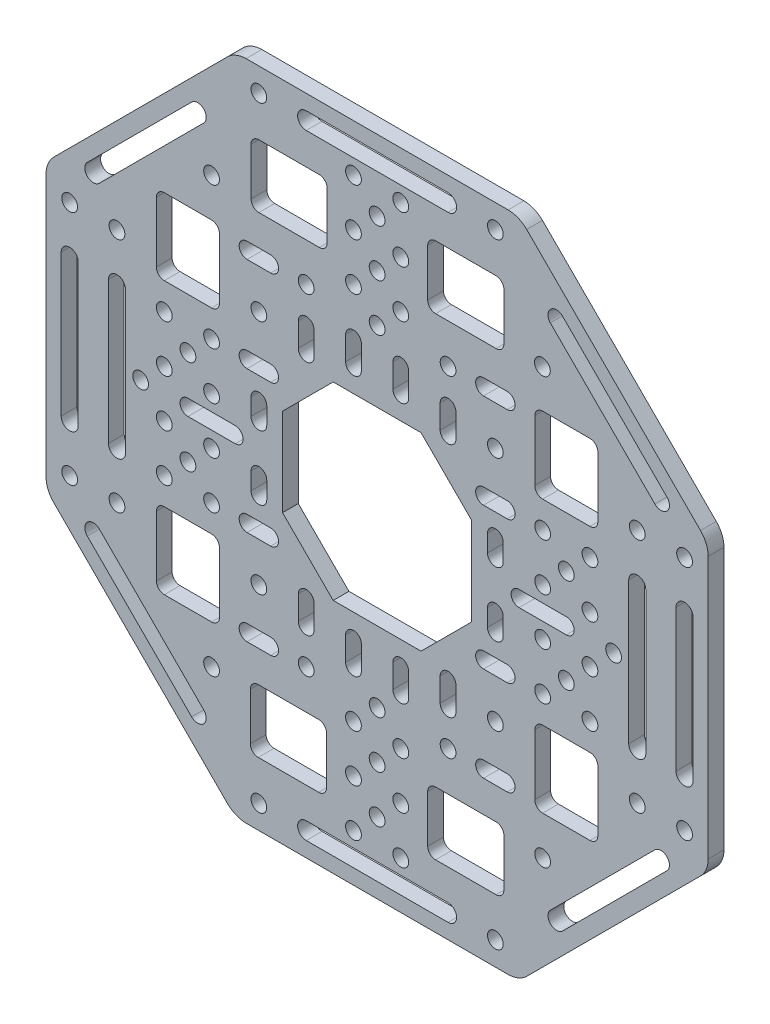
SolidWorks part; units mm, degrees
ref_plane "Alzado" through (0, 0, 0) normal (0, 0, 1) x (1, 0, 0)
ref_plane "Planta" through (0, 0, 0) normal (0, 1, 0) x (1, 0, 0)
ref_plane "Vista lateral" through (0, 0, 0) normal (1, 0, 0) x (0, 0, -1)
sketch "Model" plane through (0, 0, 0) normal (0, 0, 1) x (1, 0, 0)
  line L0 (181.0281, 257.4957) -> (131.1702, 257.4957)
  line L1 (217.6323, 222.9625) -> (184.5636, 256.0312)
  line L2 (219.0991, 169.5667) -> (219.0991, 219.4246)
  line L3 (184.5636, 132.9601) -> (217.6323, 166.0288)
  line L4 (131.1702, 131.4957) -> (181.0281, 131.4957)
  line L5 (94.566, 166.0288) -> (127.6347, 132.9601)
  line L6 (127.6347, 256.0312) -> (94.566, 222.9625)
  line L7 (174.0991, 202.8561) -> (164.4595, 212.4957)
  line L8 (174.0991, 186.1353) -> (174.0991, 202.8561)
  line L9 (164.4595, 176.4957) -> (174.0991, 186.1353)
  line L10 (147.7387, 176.4957) -> (164.4595, 176.4957)
  line L11 (138.0991, 186.1353) -> (147.7387, 176.4957)
  line L12 (138.0991, 202.8561) -> (138.0991, 186.1353)
  line L13 (147.7387, 212.4957) -> (138.0991, 202.8561)
  line L14 (164.4595, 212.4957) -> (147.7387, 212.4957)
  line L15 (93.0991, 219.4246) -> (93.0991, 169.5667)
  line L19 (142.5991, 254.6207) -> (169.5991, 254.6207)
  line L20 (169.5991, 251.3707) -> (142.5991, 251.3707)
  line L21 (123.1463, 242.8905) -> (103.2482, 222.9897)
  line L22 (100.9501, 225.2878) -> (120.7725, 245.1102)
  line L23 (95.9741, 207.9957) -> (95.9741, 180.9957)
  line L24 (99.2241, 180.9957) -> (99.2241, 207.9957)
  line L25 (104.9741, 207.9957) -> (104.9741, 180.9957)
  line L26 (108.2241, 180.9957) -> (108.2241, 207.9957)
  line L27 (203.9741, 207.9957) -> (203.9741, 180.9957)
  line L28 (207.2241, 180.9957) -> (207.2241, 207.9957)
  line L29 (212.9741, 207.9957) -> (212.9741, 180.9957)
  line L30 (216.2241, 180.9957) -> (216.2241, 207.9957)
  line L31 (208.9501, 222.9897) -> (189.052, 242.8905)
  line L32 (191.4258, 245.1102) -> (211.2482, 225.2878)
  line L33 (103.2139, 166.0348) -> (123.1041, 146.1447)
  line L34 (120.806, 143.8466) -> (100.9501, 163.7035)
  line L35 (142.5991, 137.6207) -> (169.5991, 137.6207)
  line L36 (142.5991, 134.3707) -> (169.5991, 134.3707)
  line L37 (189.0942, 146.1447) -> (208.9501, 166.0016)
  line L38 (211.2461, 163.7014) -> (191.3923, 143.8466)
  line L39 (131.3491, 227.4957) -> (135.8491, 227.4957)
  line L40 (135.8491, 224.4957) -> (131.3491, 224.4957)
  line L41 (141.0991, 219.2457) -> (141.0991, 214.7457)
  line L42 (144.0991, 214.7457) -> (144.0991, 219.2457)
  line L43 (150.0991, 221.4957) -> (150.0991, 216.9957)
  line L44 (153.0991, 216.9957) -> (153.0991, 221.4957)
  line L45 (159.0991, 221.4957) -> (159.0991, 216.9957)
  line L46 (162.0991, 216.9957) -> (162.0991, 221.4957)
  line L47 (168.0991, 219.2457) -> (168.0991, 214.7457)
  line L48 (171.0991, 214.7457) -> (171.0991, 219.2457)
  line L49 (176.3491, 224.4957) -> (180.8491, 224.4957)
  line L50 (176.3491, 227.4957) -> (180.8491, 227.4957)
  line L51 (176.3491, 209.4957) -> (180.8491, 209.4957)
  line L52 (180.8491, 206.4957) -> (176.3491, 206.4957)
  line L53 (177.0991, 202.2457) -> (177.0991, 198.9957)
  line L54 (180.0991, 198.9957) -> (180.0991, 202.2457)
  line L55 (183.0991, 195.9957) -> (192.0991, 195.9957)
  line L56 (192.0991, 192.9957) -> (183.0991, 192.9957)
  line L57 (180.0991, 189.9957) -> (180.0991, 186.7457)
  line L58 (177.0991, 186.7457) -> (177.0991, 189.9957)
  line L59 (176.3491, 182.4957) -> (180.8491, 182.4957)
  line L60 (180.8491, 179.4957) -> (176.3491, 179.4957)
  line L61 (171.0991, 174.2457) -> (171.0991, 169.7457)
  line L62 (168.0991, 169.7457) -> (168.0991, 174.2457)
  line L63 (162.0991, 171.9957) -> (162.0991, 167.4957)
  line L64 (159.0991, 167.4957) -> (159.0991, 171.9957)
  line L65 (153.0991, 171.9957) -> (153.0991, 167.4957)
  line L66 (150.0991, 167.4957) -> (150.0991, 171.9957)
  line L67 (144.0991, 174.2457) -> (144.0991, 169.7457)
  line L68 (141.0991, 169.7457) -> (141.0991, 174.2457)
  line L69 (131.3491, 164.4957) -> (135.8491, 164.4957)
  line L70 (135.8491, 161.4957) -> (131.3491, 161.4957)
  line L71 (131.3491, 179.4957) -> (135.8491, 179.4957)
  line L72 (135.8491, 182.4957) -> (131.3491, 182.4957)
  line L73 (132.0991, 186.7457) -> (132.0991, 189.9957)
  line L74 (135.0991, 189.9957) -> (135.0991, 186.7457)
  line L75 (129.0991, 192.9957) -> (120.0991, 192.9957)
  line L76 (120.0991, 195.9957) -> (129.0991, 195.9957)
  line L77 (132.0991, 202.2457) -> (132.0991, 198.9957)
  line L78 (135.0991, 198.9957) -> (135.0991, 202.2457)
  line L79 (135.8491, 206.4957) -> (131.3491, 206.4957)
  line L80 (131.3491, 209.4957) -> (135.8491, 209.4957)
  line L81 (132.1048, 243.8415) -> (132.1048, 234.8415)
  line L82 (133.6048, 233.3415) -> (145.1048, 233.3415)
  line L83 (146.6048, 234.8415) -> (146.6048, 243.8415)
  line L84 (145.1048, 245.3415) -> (133.6048, 245.3415)
  line L85 (131.9741, 153.9957) -> (131.9741, 144.9957)
  line L86 (133.4741, 143.4957) -> (144.9741, 143.4957)
  line L87 (146.4741, 144.9957) -> (146.4741, 153.9957)
  line L88 (144.9741, 155.4957) -> (133.4741, 155.4957)
  line L89 (165.7241, 153.9957) -> (165.7241, 144.9957)
  line L90 (167.2241, 143.4957) -> (178.7241, 143.4957)
  line L91 (180.2241, 144.9957) -> (180.2241, 153.9957)
  line L92 (178.7241, 155.4957) -> (167.2241, 155.4957)
  line L93 (165.7241, 243.9957) -> (165.7241, 234.9957)
  line L94 (167.2241, 233.4957) -> (178.7241, 233.4957)
  line L95 (180.2241, 234.9957) -> (180.2241, 243.9957)
  line L96 (178.7241, 245.4957) -> (167.2241, 245.4957)
  line L97 (115.5991, 213.1207) -> (124.5991, 213.1207)
  line L98 (126.0991, 214.6207) -> (126.0991, 226.1207)
  line L99 (124.5991, 227.6207) -> (115.5991, 227.6207)
  line L100 (114.0991, 226.1207) -> (114.0991, 214.6207)
  line L101 (115.5991, 161.3707) -> (124.5991, 161.3707)
  line L102 (126.0991, 162.8707) -> (126.0991, 174.3707)
  line L103 (124.5991, 175.8707) -> (115.5991, 175.8707)
  line L104 (114.0991, 174.3707) -> (114.0991, 162.8707)
  line L105 (187.5991, 213.1207) -> (196.5991, 213.1207)
  line L106 (198.0991, 214.6207) -> (198.0991, 226.1207)
  line L107 (196.5991, 227.6207) -> (187.5991, 227.6207)
  line L108 (186.0991, 226.1207) -> (186.0991, 214.6207)
  line L109 (187.5991, 161.3707) -> (196.5991, 161.3707)
  line L110 (198.0991, 162.8707) -> (198.0991, 174.3707)
  line L111 (196.5991, 175.8707) -> (187.5991, 175.8707)
  line L112 (186.0991, 174.3707) -> (186.0991, 162.8707)
  line L113 (176.3491, 164.4957) -> (180.8491, 164.4957)
  line L114 (176.3491, 161.4957) -> (180.8491, 161.4957)
  arc A0 (131.1702, 257.4957) -> (127.6347, 256.0312) centre (131.2301, 252.3511) ccw
  arc A1 (184.5636, 256.0312) -> (181.0281, 257.4957) centre (180.9681, 252.3511) ccw
  arc A2 (219.0991, 219.4246) -> (217.6323, 222.9625) centre (214.0991, 219.4246) ccw
  arc A3 (217.6323, 166.0288) -> (219.0991, 169.5667) centre (214.0991, 169.5667) ccw
  arc A4 (181.0281, 131.4957) -> (184.5636, 132.9601) centre (180.9682, 136.6403) ccw
  arc A5 (127.6347, 132.9601) -> (131.1702, 131.4957) centre (131.2301, 136.6403) ccw
  arc A6 (93.0991, 169.5667) -> (94.566, 166.0288) centre (98.0991, 169.5667) ccw
  arc A7 (94.566, 222.9625) -> (93.0991, 219.4246) centre (98.0991, 219.4246) ccw
  arc A8 (95.9741, 180.9957) -> (99.2241, 180.9957) centre (97.5991, 180.9957) ccw
  arc A9 (99.2241, 207.9957) -> (95.9741, 207.9957) centre (97.5991, 207.9957) ccw
  arc A10 (192.0991, 192.9957) -> (192.0991, 195.9957) centre (192.0991, 194.4957) ccw
  arc A11 (183.0991, 195.9957) -> (183.0991, 192.9957) centre (183.0991, 194.4957) ccw
  arc A12 (177.0991, 198.9957) -> (180.0991, 198.9957) centre (178.5991, 198.9957) ccw
  arc A13 (180.0991, 202.2457) -> (177.0991, 202.2457) centre (178.5991, 202.2457) ccw
  arc A14 (177.0991, 186.7457) -> (180.0991, 186.7457) centre (178.5991, 186.7457) ccw
  arc A15 (180.0991, 189.9957) -> (177.0991, 189.9957) centre (178.5991, 189.9957) ccw
  circle A16 centre (120.0991, 185.4957) radius 1.5
  circle A17 centre (120.0991, 203.4957) radius 1.5
  circle A18 centre (192.0991, 203.4957) radius 1.5
  circle A19 centre (192.0991, 185.4957) radius 1.5
  arc A20 (132.0991, 198.9957) -> (135.0991, 198.9957) centre (133.5991, 198.9957) ccw
  arc A21 (135.0991, 202.2457) -> (132.0991, 202.2457) centre (133.5991, 202.2457) ccw
  arc A22 (132.0991, 186.7457) -> (135.0991, 186.7457) centre (133.5991, 186.7457) ccw
  arc A23 (135.0991, 189.9957) -> (132.0991, 189.9957) centre (133.5991, 189.9957) ccw
  circle A24 centre (187.5991, 189.9957) radius 1.5
  circle A25 centre (187.5991, 198.9957) radius 1.5
  circle A26 centre (124.5991, 189.9957) radius 1.5
  circle A27 centre (124.5991, 198.9957) radius 1.5
  circle A28 centre (187.5991, 153.9957) radius 1.5
  circle A29 centre (160.5991, 149.4957) radius 1.5
  circle A30 centre (151.5991, 149.4957) radius 1.5
  circle A31 centre (156.0991, 153.9957) radius 1.5
  circle A32 centre (156.0991, 144.9957) radius 1.5
  circle A33 centre (124.5991, 153.9957) radius 1.5
  circle A34 centre (187.5991, 180.9957) radius 1.5
  circle A35 centre (196.5991, 180.9957) radius 1.5
  circle A36 centre (205.5991, 171.9957) radius 1.5
  circle A37 centre (196.5991, 198.9957) radius 1.5
  circle A38 centre (201.0991, 194.4957) radius 1.5
  circle A39 centre (196.5991, 189.9957) radius 1.5
  circle A40 centre (187.5991, 207.9957) radius 1.5
  circle A41 centre (196.5991, 207.9957) radius 1.5
  circle A42 centre (205.5991, 216.9957) radius 1.5
  circle A43 centre (187.552, 234.9195) radius 1.5
  circle A44 centre (169.5991, 162.9957) radius 1.5
  circle A45 centre (178.5991, 171.9957) radius 1.5
  circle A46 centre (133.5991, 171.9957) radius 1.5
  circle A47 centre (142.5991, 162.9957) radius 1.5
  circle A48 centre (156.0991, 162.9957) radius 1.5
  circle A49 centre (160.5991, 230.4957) radius 1.5
  circle A50 centre (178.5991, 216.9957) radius 1.5
  circle A51 centre (169.5991, 225.9957) radius 1.5
  circle A52 centre (160.5991, 239.4957) radius 1.5
  circle A53 centre (133.5991, 216.9957) radius 1.5
  circle A54 centre (142.5991, 225.9957) radius 1.5
  circle A55 centre (151.5991, 230.4957) radius 1.5
  circle A56 centre (151.5991, 239.4957) radius 1.5
  circle A57 centre (156.0991, 243.9957) radius 1.5
  circle A58 centre (156.0991, 225.9957) radius 1.5
  circle A59 centre (156.0991, 234.9957) radius 1.5
  circle A60 centre (106.5991, 171.9957) radius 1.5
  circle A61 centre (115.5991, 180.9957) radius 1.5
  circle A62 centre (124.5991, 180.9957) radius 1.5
  circle A63 centre (115.5991, 198.9957) radius 1.5
  circle A64 centre (115.5991, 189.9957) radius 1.5
  circle A65 centre (111.0991, 194.4957) radius 1.5
  circle A66 centre (106.5991, 216.9957) radius 1.5
  circle A67 centre (124.5991, 234.9957) radius 1.5
  circle A68 centre (115.5991, 207.9957) radius 1.5
  circle A69 centre (124.5991, 207.9957) radius 1.5
  circle A70 centre (151.5991, 158.4957) radius 1.5
  circle A71 centre (160.5991, 158.4957) radius 1.5
  arc A72 (144.0991, 219.2457) -> (141.0991, 219.2457) centre (142.5991, 219.2457) ccw
  arc A73 (141.0991, 214.7457) -> (144.0991, 214.7457) centre (142.5991, 214.7457) ccw
  arc A74 (135.8491, 161.4957) -> (135.8491, 164.4957) centre (135.8491, 162.9957) ccw
  arc A75 (131.3491, 164.4957) -> (131.3491, 161.4957) centre (131.3491, 162.9957) ccw
  arc A76 (216.2241, 207.9957) -> (212.9741, 207.9957) centre (214.5991, 207.9957) ccw
  arc A77 (212.9741, 180.9957) -> (216.2241, 180.9957) centre (214.5991, 180.9957) ccw
  arc A78 (207.2241, 207.9957) -> (203.9741, 207.9957) centre (205.5991, 207.9957) ccw
  arc A79 (203.9741, 180.9957) -> (207.2241, 180.9957) centre (205.5991, 180.9957) ccw
  arc A80 (142.5991, 137.6207) -> (142.5991, 134.3707) centre (142.5991, 135.9957) ccw
  arc A81 (169.5991, 134.3707) -> (169.5991, 137.6207) centre (169.5991, 135.9957) ccw
  arc A82 (176.3491, 227.4957) -> (176.3491, 224.4957) centre (176.3491, 225.9957) ccw
  arc A83 (180.8491, 224.4957) -> (180.8491, 227.4957) centre (180.8491, 225.9957) ccw
  arc A84 (176.3491, 209.4957) -> (176.3491, 206.4957) centre (176.3491, 207.9957) ccw
  arc A85 (180.8491, 206.4957) -> (180.8491, 209.4957) centre (180.8491, 207.9957) ccw
  arc A86 (176.3491, 182.4957) -> (176.3491, 179.4957) centre (176.3491, 180.9957) ccw
  arc A87 (180.8491, 179.4957) -> (180.8491, 182.4957) centre (180.8491, 180.9957) ccw
  arc A88 (176.3491, 164.4957) -> (176.3491, 161.4957) centre (176.3491, 162.9957) ccw
  arc A89 (180.8491, 161.4957) -> (180.8491, 164.4957) centre (180.8491, 162.9957) ccw
  arc A90 (168.0991, 169.7457) -> (171.0991, 169.7457) centre (169.5991, 169.7457) ccw
  arc A91 (171.0991, 174.2457) -> (168.0991, 174.2457) centre (169.5991, 174.2457) ccw
  arc A92 (171.0991, 219.2457) -> (168.0991, 219.2457) centre (169.5991, 219.2457) ccw
  arc A93 (168.0991, 214.7457) -> (171.0991, 214.7457) centre (169.5991, 214.7457) ccw
  arc A94 (142.5991, 254.6207) -> (142.5991, 251.3707) centre (142.5991, 252.9957) ccw
  arc A95 (169.5991, 251.3707) -> (169.5991, 254.6207) centre (169.5991, 252.9957) ccw
  arc A96 (159.0991, 167.4957) -> (162.0991, 167.4957) centre (160.5991, 167.4957) ccw
  arc A97 (162.0991, 171.9957) -> (159.0991, 171.9957) centre (160.5991, 171.9957) ccw
  arc A98 (162.0991, 221.4957) -> (159.0991, 221.4957) centre (160.5991, 221.4957) ccw
  arc A99 (159.0991, 216.9957) -> (162.0991, 216.9957) centre (160.5991, 216.9957) ccw
  arc A100 (153.0991, 221.4957) -> (150.0991, 221.4957) centre (151.5991, 221.4957) ccw
  arc A101 (150.0991, 216.9957) -> (153.0991, 216.9957) centre (151.5991, 216.9957) ccw
  arc A102 (150.0991, 167.4957) -> (153.0991, 167.4957) centre (151.5991, 167.4957) ccw
  arc A103 (153.0991, 171.9957) -> (150.0991, 171.9957) centre (151.5991, 171.9957) ccw
  arc A104 (141.0991, 169.7457) -> (144.0991, 169.7457) centre (142.5991, 169.7457) ccw
  arc A105 (144.0991, 174.2457) -> (141.0991, 174.2457) centre (142.5991, 174.2457) ccw
  arc A106 (135.8491, 224.4957) -> (135.8491, 227.4957) centre (135.8491, 225.9957) ccw
  arc A107 (131.3491, 227.4957) -> (131.3491, 224.4957) centre (131.3491, 225.9957) ccw
  arc A108 (135.8491, 206.4957) -> (135.8491, 209.4957) centre (135.8491, 207.9957) ccw
  arc A109 (131.3491, 209.4957) -> (131.3491, 206.4957) centre (131.3491, 207.9957) ccw
  arc A110 (135.8491, 179.4957) -> (135.8491, 182.4957) centre (135.8491, 180.9957) ccw
  arc A111 (131.3491, 182.4957) -> (131.3491, 179.4957) centre (131.3491, 180.9957) ccw
  arc A112 (129.0991, 192.9957) -> (129.0991, 195.9957) centre (129.0991, 194.4957) ccw
  arc A113 (120.0991, 195.9957) -> (120.0991, 192.9957) centre (120.0991, 194.4957) ccw
  arc A114 (108.2241, 207.9957) -> (104.9741, 207.9957) centre (106.5991, 207.9957) ccw
  arc A115 (104.9741, 180.9957) -> (108.2241, 180.9957) centre (106.5991, 180.9957) ccw
  circle A116 centre (160.5991, 248.4957) radius 1.5
  circle A117 centre (151.5991, 248.4957) radius 1.5
  circle A118 centre (160.5991, 140.4957) radius 1.5
  circle A119 centre (151.5991, 140.4957) radius 1.5
  circle A120 centre (97.5991, 216.9957) radius 1.5
  circle A121 centre (97.5991, 171.9957) radius 1.5
  circle A122 centre (214.5991, 171.9957) radius 1.5
  circle A123 centre (214.5991, 216.9957) radius 1.5
  circle A124 centre (133.5991, 135.9957) radius 1.5
  circle A125 centre (178.5991, 135.9957) radius 1.5
  circle A126 centre (178.5991, 252.9957) radius 1.5
  circle A127 centre (133.5991, 252.9957) radius 1.5
  arc A128 (211.2461, 163.7014) -> (208.9501, 166.0016) centre (210.0981, 164.8515) ccw
  arc A129 (208.9501, 222.9897) -> (211.2482, 225.2878) centre (210.0991, 224.1388) ccw
  arc A130 (103.2139, 166.0348) -> (100.9501, 163.7035) centre (102.1001, 164.8516) ccw
  arc A131 (100.9501, 225.2878) -> (103.2482, 222.9897) centre (102.0991, 224.1388) ccw
  arc A132 (191.4258, 245.1102) -> (189.052, 242.8905) centre (190.2389, 244.0003) ccw
  arc A133 (123.1463, 242.8905) -> (120.7725, 245.1102) centre (121.9594, 244.0003) ccw
  arc A134 (189.0942, 146.1447) -> (191.3923, 143.8466) centre (190.2432, 144.9957) ccw
  arc A135 (120.806, 143.8466) -> (123.1041, 146.1447) centre (121.955, 144.9957) ccw
  arc A136 (146.6048, 243.8415) -> (145.1048, 245.3415) centre (145.1048, 243.8415) ccw
  arc A137 (145.1048, 233.3415) -> (146.6048, 234.8415) centre (145.1048, 234.8415) ccw
  arc A138 (132.1048, 234.8415) -> (133.6048, 233.3415) centre (133.6048, 234.8415) ccw
  arc A139 (133.6048, 245.3415) -> (132.1048, 243.8415) centre (133.6048, 243.8415) ccw
  arc A140 (146.4741, 153.9957) -> (144.9741, 155.4957) centre (144.9741, 153.9957) ccw
  arc A141 (144.9741, 143.4957) -> (146.4741, 144.9957) centre (144.9741, 144.9957) ccw
  arc A142 (131.9741, 144.9957) -> (133.4741, 143.4957) centre (133.4741, 144.9957) ccw
  arc A143 (133.4741, 155.4957) -> (131.9741, 153.9957) centre (133.4741, 153.9957) ccw
  arc A144 (180.2241, 153.9957) -> (178.7241, 155.4957) centre (178.7241, 153.9957) ccw
  arc A145 (178.7241, 143.4957) -> (180.2241, 144.9957) centre (178.7241, 144.9957) ccw
  arc A146 (165.7241, 144.9957) -> (167.2241, 143.4957) centre (167.2241, 144.9957) ccw
  arc A147 (167.2241, 155.4957) -> (165.7241, 153.9957) centre (167.2241, 153.9957) ccw
  arc A148 (180.2241, 243.9957) -> (178.7241, 245.4957) centre (178.7241, 243.9957) ccw
  arc A149 (178.7241, 233.4957) -> (180.2241, 234.9957) centre (178.7241, 234.9957) ccw
  arc A150 (165.7241, 234.9957) -> (167.2241, 233.4957) centre (167.2241, 234.9957) ccw
  arc A151 (167.2241, 245.4957) -> (165.7241, 243.9957) centre (167.2241, 243.9957) ccw
  arc A152 (115.5991, 227.6207) -> (114.0991, 226.1207) centre (115.5991, 226.1207) ccw
  arc A153 (126.0991, 226.1207) -> (124.5991, 227.6207) centre (124.5991, 226.1207) ccw
  arc A154 (124.5991, 213.1207) -> (126.0991, 214.6207) centre (124.5991, 214.6207) ccw
  arc A155 (114.0991, 214.6207) -> (115.5991, 213.1207) centre (115.5991, 214.6207) ccw
  arc A156 (115.5991, 175.8707) -> (114.0991, 174.3707) centre (115.5991, 174.3707) ccw
  arc A157 (126.0991, 174.3707) -> (124.5991, 175.8707) centre (124.5991, 174.3707) ccw
  arc A158 (124.5991, 161.3707) -> (126.0991, 162.8707) centre (124.5991, 162.8707) ccw
  arc A159 (114.0991, 162.8707) -> (115.5991, 161.3707) centre (115.5991, 162.8707) ccw
  arc A160 (187.5991, 227.6207) -> (186.0991, 226.1207) centre (187.5991, 226.1207) ccw
  arc A161 (198.0991, 226.1207) -> (196.5991, 227.6207) centre (196.5991, 226.1207) ccw
  arc A162 (196.5991, 213.1207) -> (198.0991, 214.6207) centre (196.5991, 214.6207) ccw
  arc A163 (186.0991, 214.6207) -> (187.5991, 213.1207) centre (187.5991, 214.6207) ccw
  arc A164 (187.5991, 175.8707) -> (186.0991, 174.3707) centre (187.5991, 174.3707) ccw
  arc A165 (198.0991, 174.3707) -> (196.5991, 175.8707) centre (196.5991, 174.3707) ccw
  arc A166 (196.5991, 161.3707) -> (198.0991, 162.8707) centre (196.5991, 162.8707) ccw
  arc A167 (186.0991, 162.8707) -> (187.5991, 161.3707) centre (187.5991, 162.8707) ccw
extrude "Saliente-Extruir1" add sketch "Model" along normal blind 3
